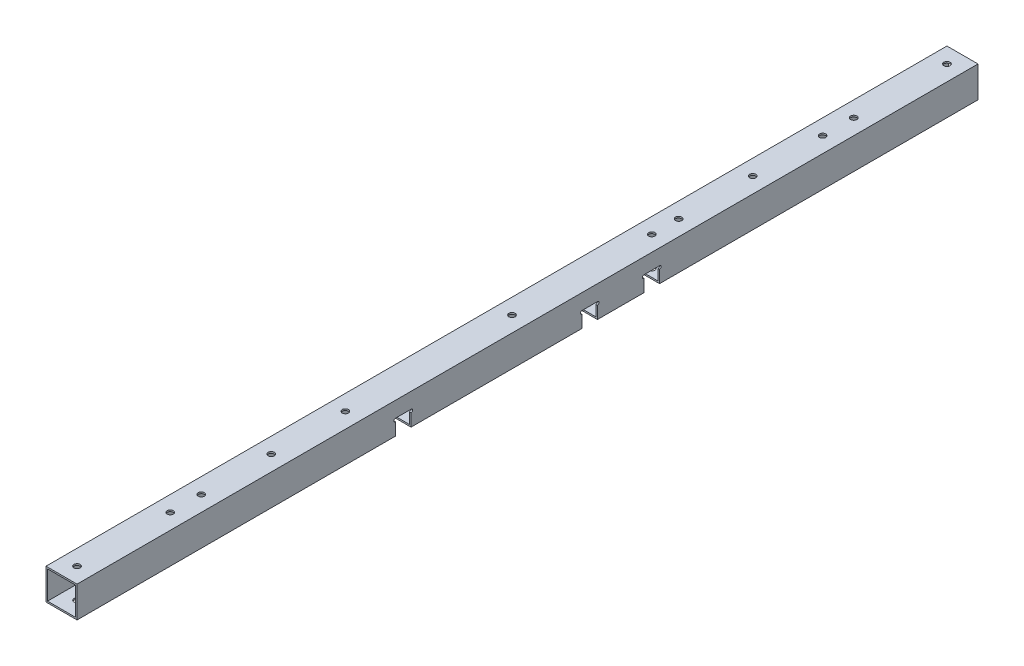
SolidWorks part; units mm, degrees
ref_plane "前视基准面" through (0, 0, 0) normal (0, 0, 1) x (1, 0, 0)
ref_plane "上视基准面" through (0, 0, 0) normal (0, 1, 0) x (1, 0, 0)
ref_plane "右视基准面" through (0, 0, 0) normal (1, 0, 0) x (0, 0, -1)
sketch "草图1" plane through (0, 0, 0) normal (0, 0, 1) x (1, 0, 0)
  line L1 (-10, 10) -> (10, 10)
  line L2 (-10, 10) -> (-10, -10)
  line L3 (-10, -10) -> (10, -10)
  line L4 (10, 10) -> (10, -10)
  line L5 (-10, 10) -> (10, -10) construction
  line L6 (-10, -10) -> (10, 10) construction
  line L7 (-9, 9) -> (9, 9)
  line L8 (-9, 9) -> (-9, -9)
  line L9 (-9, -9) -> (9, -9)
  line L10 (9, 9) -> (9, -9)
  line L11 (-9, 9) -> (9, -9) construction
  line L12 (-9, -9) -> (9, 9) construction
  point P0 (0, 0)
  point P6 (0, 0)
extrude "凸台-拉伸1" add sketch "草图1" along normal mid plane 580
ref_plane "基准面1" through (0, 0, 0) normal (0, 0, 1) x (1, 0, 0)
hole_wizard "Ø4.0 (4) 直径孔1" positions "草图3" profile "草图2" hole size "Ø4.0" standard "GB" end condition through all
sketch "草图3" plane through (0, 10, 0) normal (0, 1, 0) x (1, 0, 0)
  line L0 (0, 0) -> (0, 155)
  point P0 (0, 155)
sketch "草图2" plane through (0, 10, -155) normal (1, 0, 0) x (0, 0, 1)
  line L0 (0, 0) -> (0, 20)
  line L1 (0, 20) -> (2, 20)
  line L2 (2, 20) -> (2, 0)
  line L5 (2, 0) -> (0, 0)
  line L11 (0, -6.35) -> (0, 107.95) construction
  dimension "通孔孔直径" = 4
  dimension "通孔孔深度" = 20
mirror "镜向1" about plane through (0, 0, 0) normal (0, 0, 1) of "Ø4.0 (4) 直径孔1"
hole_wizard "Ø4.0 (4) 直径孔2" positions "草图5" profile "草图4" hole size "Ø4.0" standard "GB" end condition through all
sketch "草图5" plane through (0, 10, 0) normal (0, 1, 0) x (1, 0, 0)
  line L2 (0, 290) -> (0, 280)
  line L3 (10, 290) -> (-10, 290) construction
  point P13 (0, 280)
sketch "草图4" plane through (0, 10, -280) normal (1, 0, 0) x (0, 0, 1)
  line L0 (0, 0) -> (0, 20)
  line L1 (0, 20) -> (2, 20)
  line L2 (2, 20) -> (2, 0)
  line L5 (2, 0) -> (0, 0)
  line L11 (0, -6.35) -> (0, 107.95) construction
  dimension "通孔孔直径" = 4
  dimension "通孔孔深度" = 20
mirror "镜向2" about plane through (0, 0, 0) normal (0, 0, 1) of "Ø4.0 (4) 直径孔2"
hole_wizard "Ø4.0 (4) 直径孔3" positions "草图7" profile "草图6" hole size "Ø4.0" standard "GB" end condition through all
sketch "草图7" plane through (0, -10, 0) normal (0, -1, 0) x (-1, 0, 0)
  line L6 (0, 290) -> (0, 200)
  line L7 (10, 290) -> (-10, 290) construction
  point P0 (0, 220)
  point P15 (0, 200)
sketch "草图6" plane through (0, -10, -220) normal (1, 0, 0) x (0, 0, -1)
  line L0 (0, 0) -> (0, 20)
  line L1 (0, 20) -> (2, 20)
  line L2 (2, 20) -> (2, 0)
  line L5 (2, 0) -> (0, 0)
  line L11 (0, -6.35) -> (0, 107.95) construction
  dimension "通孔孔直径" = 4
  dimension "通孔孔深度" = 20
hole_wizard "Ø4.0 (4) 直径孔4" positions "草图9" profile "草图8" hole size "Ø4.0" standard "GB" end condition through all
sketch "草图9" plane through (0, 10, 0) normal (0, 1, 0) x (1, 0, 0)
  line L0 (0, 90) -> (0, 290)
  line L1 (10, 290) -> (-10, 290) construction
  point P0 (0, 90)
sketch "草图8" plane through (0, 10, -90) normal (1, 0, 0) x (0, 0, 1)
  line L0 (0, 0) -> (0, 20)
  line L1 (0, 20) -> (2, 20)
  line L2 (2, 20) -> (2, 0)
  line L5 (2, 0) -> (0, 0)
  line L11 (0, -6.35) -> (0, 107.95) construction
  dimension "通孔孔直径" = 4
  dimension "通孔孔深度" = 20
mirror "镜向3" about plane through (0, 0, 0) normal (0, 0, 1) of "Ø4.0 (4) 直径孔3"
hole_wizard "Ø4.0 (4) 直径孔6" positions "草图11" profile "草图10" hole size "Ø4.0" standard "GB"
sketch "草图11" plane through (0, 10, 0) normal (0, 1, 0) x (1, 0, 0)
  line L0 (0, 290) -> (0, 107.3)
  line L1 (10, 290) -> (-10, 290) construction
  point P2 (0, 107.3)
sketch "草图10" plane through (0, 10, -107.3) normal (1, 0, 0) x (0, 0, 1)
  line L0 (0, 0) -> (0, 20)
  line L1 (0, 20) -> (2, 20)
  line L2 (2, 20) -> (2, 0)
  line L5 (2, 0) -> (0, 0)
  line L11 (0, -6.35) -> (0, 107.95) construction
  dimension "通孔孔直径" = 4
  dimension "通孔孔深度" = 20
mirror "镜向4" about plane through (0, 0, 0) normal (0, 0, 1) of "Ø4.0 (4) 直径孔6"
hole_wizard "Ø13.0 (13) 直径孔1" positions "草图13" profile "草图12" hole size "Ø13.0" standard "GB"
sketch "草图13" plane through (0, -9, 0) normal (0, 1, 0) x (1, 0, 0)
  line L0 (0, 290) -> (0, 107.3)
  line L1 (-9, 290) -> (9, 290) construction
  point P2 (0, 107.3)
sketch "草图12" plane through (0, -9, -107.3) normal (1, 0, 0) x (0, 0, 1)
  line L0 (0, 0) -> (0, 1.001)
  line L1 (0, 1.001) -> (6.5, 1.001)
  line L2 (6.5, 1.001) -> (6.5, 0)
  line L5 (6.5, 0) -> (0, 0)
  line L11 (0, -6.35) -> (0, 107.95) construction
  dimension "通孔孔直径" = 13
  dimension "通孔孔深度" = 1.001
mirror "镜向5" about plane through (0, 0, 0) normal (0, 0, 1) of "Ø13.0 (13) 直径孔1"
sketch "草图14" plane through (0, -10, 0) normal (0, -1, 0) x (1, 0, 0)
  line L0 (0, -90) -> (0, -70) construction
  line L1 (0, -80) -> (-10, -80)
  line L2 (-10, 290) -> (-10, -290) construction
  line L3 (-10, -80) -> (-10, -85)
  line L4 (-10, -85) -> (10, -85)
  line L5 (10, 290) -> (10, -290) construction
  line L6 (10, -85) -> (10, -75)
  line L7 (10, -75) -> (-10, -75)
  line L8 (-10, -75) -> (-10, -80)
  line M13 (10, -290) -> (10, 290)
  line M15 (-10, 290) -> (-10, -290)
extrude "切除-拉伸1" cut sketch "草图14" against normal blind 10 contours L4 L0 L1 M15 | L1 L0 L7 M15 | L0 L4 L7 M13
sketch "草图17" plane through (10, 0, 0) normal (1, 0, 0) x (0, 0, -1)
  line L0 (85, -1) -> (85, 0)
  line L1 (85, 0) -> (85, -10) construction
  circle A0 centre (85, -1) radius 1
extrude "切除-拉伸3" cut sketch "草图17" against normal blind 20 contours A0
pattern_linear "阵列(线性)1" count 2 spacing 10 along (0, 0, 1) of "切除-拉伸3"
pattern_linear "阵列(线性)2" count 2 spacing 40 along (0, 0, 1) of "切除-拉伸1", "切除-拉伸3", "阵列(线性)1"
pattern_linear "阵列(线性)3" count 2 spacing 160 along (0, 0, 1) of "切除-拉伸1", "切除-拉伸3", "阵列(线性)1"
hole_wizard "Ø4.0 (4) 直径孔7" positions "草图19" profile "草图18" hole size "Ø4.0" standard "GB" end condition through all
sketch "草图19" plane through (0, -10, 0) normal (0, -1, 0) x (-1, 0, 0)
  line L0 (0, 0) -> (0, 290)
  line L1 (10, 290) -> (-10, 290) construction
  point P0 (0, 0)
sketch "草图18" plane through (0, -10, 0) normal (1, 0, 0) x (0, 0, -1)
  line L0 (0, 0) -> (0, 20)
  line L1 (0, 20) -> (2, 20)
  line L2 (2, 20) -> (2, 0)
  line L5 (2, 0) -> (0, 0)
  line L11 (0, -6.35) -> (0, 107.95) construction
  dimension "通孔孔直径" = 4
  dimension "通孔孔深度" = 20
